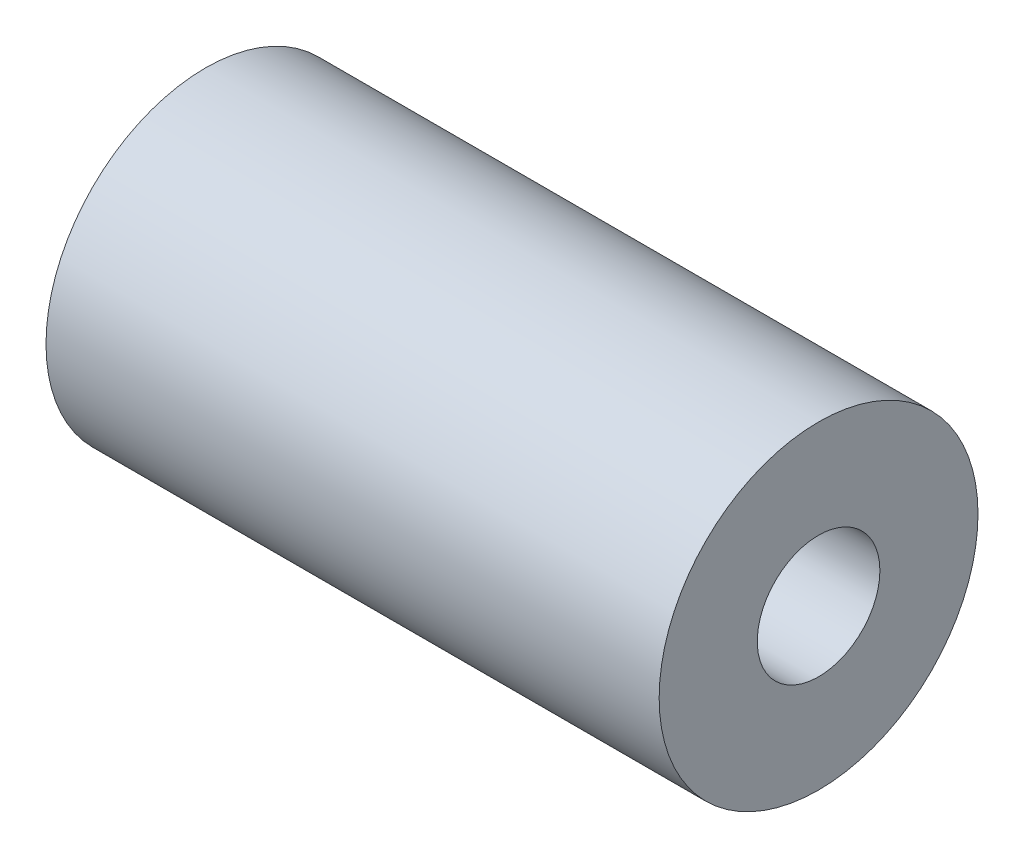
SolidWorks part; units mm, degrees
ref_plane "Front Plane" through (0, 0, 0) normal (0, 0, 1) x (1, 0, 0)
ref_plane "Top Plane" through (0, 0, 0) normal (0, 1, 0) x (1, 0, 0)
ref_plane "Right Plane" through (0, 0, 0) normal (1, 0, 0) x (0, 0, -1)
sketch "Sketch1" plane through (0, 0, 0) normal (1, 0, 0) x (0, 0, -1)
  circle A0 centre (0, 0) radius 6.5
  dimension "D1" = 13
extrude "Boss-Extrude1" add sketch "Sketch1" along normal mid plane 25
sketch "Sketch2" plane through (12.5, 0, 0) normal (1, 0, 0) x (0, 0, -1)
  circle A0 centre (0, 0) radius 2.5
  dimension "D1" = 5
extrude "Cut-Extrude1" cut sketch "Sketch2" against normal blind 12.5
sketch "Sketch3" plane through (-12.5, 0, 0) normal (-1, 0, 0) x (0, 0, 1)
  circle A0 centre (0, 0) radius 4
  dimension "D1" = 8
extrude "Cut-Extrude2" cut sketch "Sketch3" against normal blind 12.5
